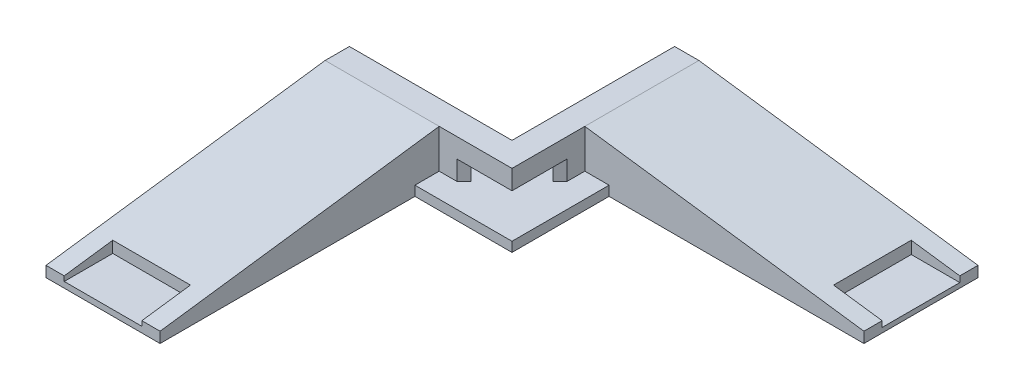
SolidWorks part; units mm, degrees
ref_plane "Front Plane" through (0, 0, 0) normal (0, 0, 1) x (1, 0, 0)
ref_plane "Top Plane" through (0, 0, 0) normal (0, 1, 0) x (1, 0, 0)
ref_plane "Right Plane" through (0, 0, 0) normal (1, 0, 0) x (0, 0, -1)
sketch "Sketch1" plane through (0, 0, 0) normal (0, 1, 0) x (1, 0, 0)
  line L0 (23, -85.5339) -> (23, -95.5339)
  line L1 (23, -85.5339) -> (56.5, -85.5339)
  line L4 (56.5, -85.5339) -> (56.5, -52.0339)
  line L7 (46.5, -95.5339) -> (66.5, -95.5339)
  line L8 (66.5, -95.5339) -> (66.5, -75.5339)
  line L9 (66.5, -52.0339) -> (56.5, -52.0339)
  line L11 (23, -95.5339) -> (23, -158.0339)
  line L12 (23, -158.0339) -> (46.5, -158.0339)
  line L13 (46.5, -95.5339) -> (46.5, -158.0339)
  line L14 (66.5, -52.0339) -> (129, -52.0339)
  line L16 (66.5, -75.5339) -> (129, -75.5339)
  line L17 (129, -52.0339) -> (129, -75.5339)
  point P0 (0, 0)
  dimension "D1" = 23.5
  dimension "D2" = 62.5
  dimension "D3" = 10
  dimension "D4" = 10
  dimension "D5" = 33.5
  dimension "D6" = 33.5
  dimension "D7" = 62.5
  dimension "D8" = 23.5
extrude "Boss-Extrude1" add sketch "Sketch1" along normal blind 2
sketch "Sketch2" plane through (0, 2, 0) normal (0, 1, 0) x (1, 0, 0)
  line L0 (56.5, -52.0339) -> (61.5, -52.0339)
  line L1 (129, -52.0339) -> (56.5, -52.0339) construction
  line L2 (61.5, -52.0339) -> (61.5, -90.5339)
  line L3 (61.5, -90.5339) -> (23, -90.5339)
  line L4 (23, -85.5339) -> (23, -158.0339) construction
  line L5 (23, -90.5339) -> (23, -85.5339)
  line L6 (23, -85.5339) -> (56.5, -85.5339)
  line L7 (56.5, -85.5339) -> (56.5, -52.0339)
  dimension "D1" = 5
  dimension "D2" = 5
extrude "Boss-Extrude2" add sketch "Sketch2" along normal blind 8
sketch "Sketch7" plane through (0, 2, 0) normal (0, 1, 0) x (1, 0, 0)
  line L0 (129, -75.5339) -> (129, -52.0339) construction
  line L1 (129, -55.7839) -> (109, -55.7839)
  line L2 (129, -55.7839) -> (129, -71.7839)
  line L3 (129, -71.7839) -> (109, -71.7839)
  line L4 (109, -55.7839) -> (109, -71.7839)
  line L5 (129, -52.0339) -> (61.5, -52.0339) construction
  dimension "D1" = 20
  dimension "D2" = 16
  dimension "D3" = 3.75
extrude "Cut-Extrude4" cut sketch "Sketch7" against normal blind 1 contours L4 L3 L2 L1
sketch "Sketch8" plane through (0, 2, 0) normal (0, 1, 0) x (1, 0, 0)
  line L0 (46.5, -158.0339) -> (46.5, -95.5339) construction
  line L1 (23, -158.0339) -> (46.5, -158.0339)
  line L2 (23, -158.0339) -> (23, -148.0339)
  line L3 (23, -148.0339) -> (46.5, -148.0339)
  line L4 (46.5, -158.0339) -> (46.5, -148.0339)
  dimension "D1" = 10
extrude "Cut-Extrude5" cut sketch "Sketch8" against normal through all
sketch "Sketch9" plane through (0, 2, 0) normal (0, 1, 0) x (1, 0, 0)
  line L0 (66.5, -75.5339) -> (129, -75.5339) construction
  line L1 (129, -52.0339) -> (119, -52.0339)
  line L2 (129, -52.0339) -> (129, -75.5339)
  line L3 (129, -75.5339) -> (119, -75.5339)
  line L4 (119, -52.0339) -> (119, -75.5339)
  dimension "D1" = 10
extrude "Cut-Extrude6" cut sketch "Sketch9" against normal through all
sketch "Sketch11" plane through (0, 0, 90.5339) normal (0, 0, 1) x (1, 0, 0)
  line L0 (46.5, 2) -> (46.5, 10)
  line L1 (23, 10) -> (61.5, 10) construction
  line L2 (46.5, 10) -> (23, 10)
  line L3 (23, 10) -> (23, 2)
  line L4 (46.5, 2) -> (23, 2)
sketch "Sketch13" plane through (0, 0, 148.0339) normal (0, 0, 1) x (1, 0, 0)
  line L0 (23, 2) -> (23, 2.2)
  line L1 (23, 10) -> (23, 2) construction
  line L2 (23, 2.2) -> (46.5, 2.2)
  line L3 (46.5, 2) -> (46.5, 10) construction
  line L4 (46.5, 2.2) -> (46.5, 2)
  line L5 (46.5, 2) -> (23, 2)
  dimension "D1" = 0.2
loft "Loft3" add profiles "Sketch11", "Sketch13"
sketch "Sketch16" plane through (0, 0, 148.0339) normal (0, 0, 1) x (1, 0, 0)
  line L0 (46.5, 0) -> (46.5, 2) construction
  line L1 (26.75, 5.2) -> (42.75, 5.2)
  line L2 (26.75, 5.2) -> (26.75, 1.2)
  line L3 (26.75, 1.2) -> (42.75, 1.2)
  line L4 (42.75, 5.2) -> (42.75, 1.2)
  line L5 (46.5, 2.2) -> (23, 2.2) construction
  dimension "D1" = 16
  dimension "D2" = 3.75
  dimension "D3" = 4
  dimension "D4" = 1
extrude "Cut-Extrude7" cut sketch "Sketch16" against normal blind 10
ref_plane "Plane1" through (-14.5169, 0, 14.5169) normal (-0.7071, 0, 0.7071) x (0.7071, 0, 0.7071)
mirror "Mirror2" about plane through (-14.5169, 0, 14.5169) normal (-0.7071, 0, 0.7071) of "Cut-Extrude7", "Loft3"
ref_plane "Plane2" through (54.2669, 0, 54.2669) normal (0.7071, 0, 0.7071) x (0.7071, 0, -0.7071)
sketch "Sketch17" plane through (54.2669, 0, 54.2669) normal (0.7071, 0, 0.7071) x (0.7071, 0, -0.7071)
  line L0 (-20.5301, 10) -> (-20.5301, 2) construction
  line L1 (-26.5301, 6) -> (-14.5301, 6)
  line L2 (-26.5301, 6) -> (-26.5301, 2)
  line L3 (-26.5301, 2) -> (-14.5301, 2)
  line L4 (-14.5301, 6) -> (-14.5301, 2)
  point P4 (-20.5301, 2)
  dimension "D1" = 6
  dimension "D2" = 4
extrude "Cut-Extrude8" cut sketch "Sketch17" along normal through all
ref_plane "Plane3" through (-14.5169, 0, 14.5169) normal (-0.7071, 0, 0.7071) x (0.7071, 0, 0.7071)
sketch "Sketch18" plane through (-14.5169, 0, 14.5169) normal (-0.7071, 0, 0.7071) x (0.7071, 0, 0.7071)
  line L0 (101.5042, 6) -> (107.5042, 6) construction
  line L1 (113.9346, 6) -> (99.5042, 6)
  line L2 (113.9346, 6) -> (113.9346, 2)
  line L3 (113.9346, 2) -> (99.5042, 2)
  line L4 (99.5042, 6) -> (99.5042, 2)
  line L7 (101.5042, 2) -> (101.5042, 6) construction
  dimension "D1" = 4
  dimension "D2" = 2
extrude "Cut-Extrude9" cut sketch "Sketch18" against normal mid plane 18 contours L1 L4 L3 L2
